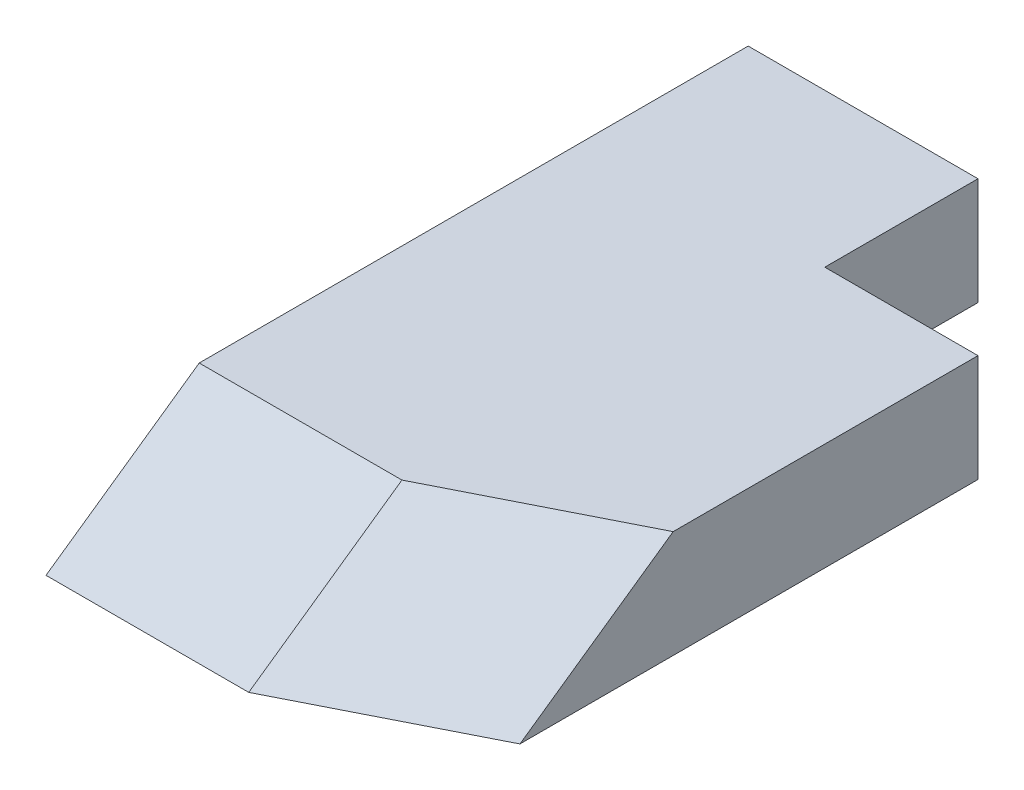
SolidWorks part; units mm, degrees
material "Plástico personalizado"
ref_plane "Front Plane" through (0, 0, 0) normal (0, 0, 1) x (1, 0, 0)
ref_plane "Top Plane" through (0, 0, 0) normal (0, 1, 0) x (1, 0, 0)
ref_plane "Right Plane" through (0, 0, 0) normal (1, 0, 0) x (0, 0, -1)
sketch "Sketch1" plane through (0, 0, 0) normal (1, 0, 0) x (0, 0, -1)
  line L0 (-28, -7) -> (15, -7)
  line L1 (15, -7) -> (15, -15.4025)
  line L5 (-28, -7) -> (-40, -15.4025)
  line L6 (-40, -15.4025) -> (15, -15.4025)
  dimension "D1" = 35
  dimension "D2" = 55
extrude "Boss-Extrude1" add sketch "Sketch1" along normal mid plane 30
ref_plane "Plane1" through (-15, -7, 28) normal (-1, 0, 0) x (0, 0, 1)
sketch "Sketch3" plane through (0, -7, 0) normal (0, 1, 0) x (1, 0, 0)
  line L0 (15, -28) -> (-15, -28) construction
  line L1 (-0.88, -28) -> (-15, -20.8768)
  line L2 (-15, 15) -> (-15, -28) construction
  line L3 (0, -28) -> (0, 15) construction
  line L4 (15, 15) -> (-15, 15) construction
  line L5 (0.88, -28) -> (15, -20.8768)
  point P0 (-0.88, -28)
  point P1 (0, -28)
  dimension "D1" = 0.88
  dimension "D2" = 26.77
sketch "Sketch4" plane through (0, 8.4586, 5.9228) normal (0, 0.8192, 0.5736) x (1, 0, 0)
  line L0 (-0.88, -26.9513) -> (-0.88, -41.6006) construction
  line L1 (15, -41.6006) -> (-15, -41.6006) construction
  line L2 (0, -26.9513) -> (0, -39.0441) construction
  line L3 (15, -26.9513) -> (-15, -26.9513) construction
  line L4 (0.88, -26.9513) -> (0.88, -41.6006) construction
  point P6 (-0.88, -41.6006)
ref_plane "Plane2" through (-2.8251, 7.9976, 5.6) normal (-0.278, 0.7869, 0.551) x (0.9606, 0.2277, 0.1594)
ref_plane "Plane3" through (2.8251, 7.9976, 5.6) normal (-0.278, -0.7869, -0.551) x (-0.9606, 0.2277, 0.1594)
sketch "Sketch6" plane through (2.8251, 7.9976, 5.6) normal (-0.278, -0.7869, -0.551) x (-0.9606, 0.2277, 0.1594)
  circle A0 centre (-5.7792, -31.9093) radius 26.8982
extrude "Cut-Extrude2" cut sketch "Sketch6" against normal blind 9
sketch "Sketch7" plane through (0, -15.4025, 0) normal (0, -1, 0) x (1, 0, 0)
  line L1 (15, -15) -> (3, -15)
  line L2 (15, -15) -> (15, -3)
  line L3 (15, -3) -> (3, -3)
  line L4 (3, -15) -> (3, -3)
  dimension "D1" = 12
  dimension "D2" = 12
extrude "Cut-Extrude3" cut sketch "Sketch7" against normal blind 10
hole_wizard "Escareado para parafuso de máquina com cabeça chata de M51" positions "Esboço1" profile "Esboço2" countersink size "M5" standard "Ansi Metric"
sketch "Esboço1" plane through (-40.125, -15.4025, -23.4602) normal (0, -1, 0) x (-1, 0, 0)
  line L4 (0, 0) -> (0, -35.8382) construction
  point P0 (33.065, -33.4602)
  point P2 (33.065, -18.4602)
  point P28 (-33.065, -18.4602)
  point P29 (-33.065, -33.4602)
  point P30 (-33.065, -33.4602)
  point P32 (-33.065, -18.4602)
sketch "Esboço2" plane through (-73.19, -15.4025, 10) normal (1, 0, 0) x (0, 0, -1)
  line L0 (0, 0) -> (0, 21.6524)
  line L1 (0, 21.6524) -> (2.75, 20)
  line L2 (2.75, 20) -> (2.75, 2.45)
  line L3 (2.75, 2.45) -> (5.2, 0)
  line L4 (5.2, 0) -> (0, 0)
  line L5 (-2.75, 2.45) -> (-5.2, 0) construction
  line L6 (0, 21.6524) -> (-2.75, 20) construction
  line L7 (0, -6.35) -> (0, 107.95) construction
  dimension "Hole Dia." = 5.5
  dimension "Hole Depth" = 20
  dimension "Near C'Sink Dia." = 10.4
  dimension "Near C'Sink Angle" = 90
  dimension "Drill Angle" = 118
